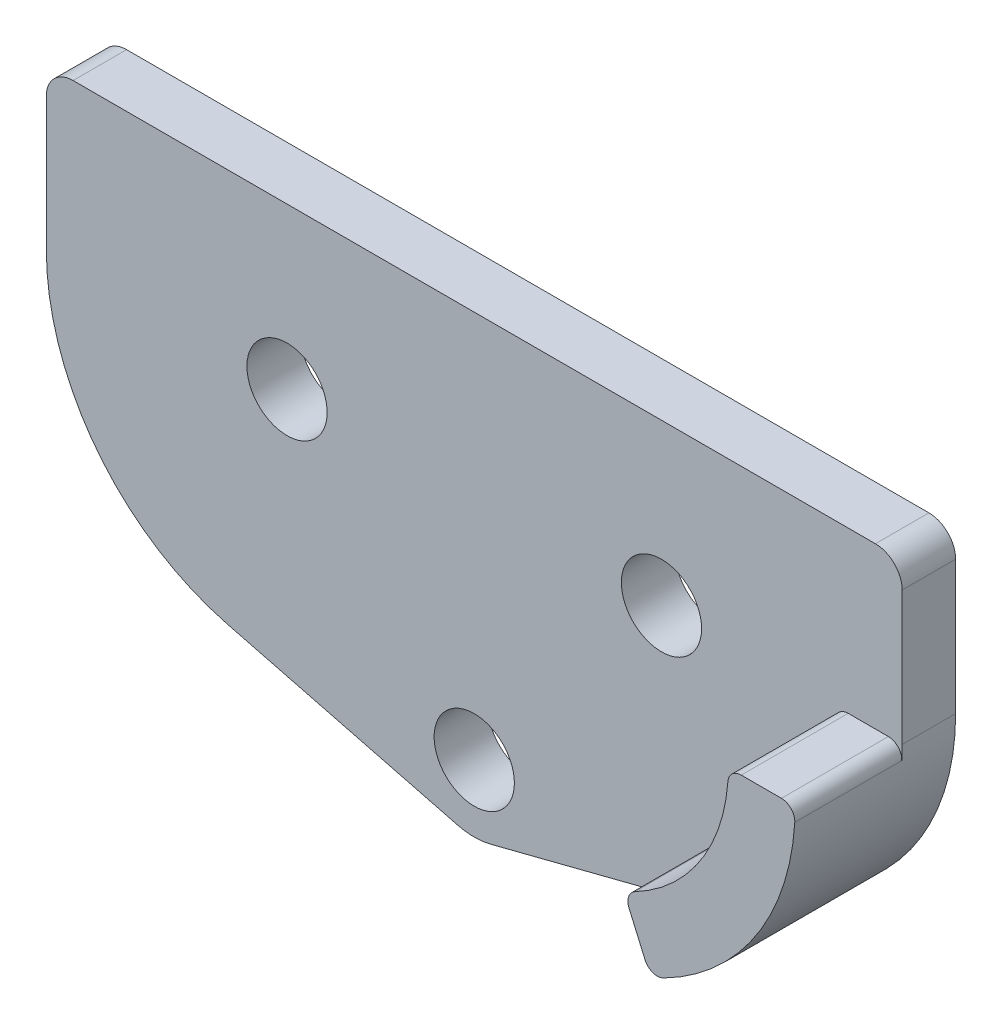
SolidWorks part; units mm, degrees
ref_plane "前视基准面" through (0, 0, 0) normal (0, 0, 1) x (1, 0, 0)
ref_plane "上视基准面" through (0, 0, 0) normal (0, 1, 0) x (1, 0, 0)
ref_plane "右视基准面" through (0, 0, 0) normal (1, 0, 0) x (0, 0, -1)
sketch "草图2" plane through (0, 0, 0) normal (0, 0, 1) x (1, 0, 0)
  line L0 (0, 6.5192) -> (0, -8.5) construction
  line L1 (0, 0) -> (7, 0) construction
  line L2 (0, -6) -> (7, -6) construction
  line L3 (7, 6) -> (-7, 6)
  line L4 (16, 0) -> (16, 6)
  line L5 (16, 6) -> (7, 6)
  line L6 (9.2305, -8.7192) -> (0.6196, -10.922)
  line L7 (0, -8.5) -> (0, -16) construction
  line L8 (-9.2305, -8.7192) -> (-0.6196, -10.922)
  line L9 (-16, 0) -> (-16, 6)
  line L10 (-16, 6) -> (-7, 6)
  circle A0 centre (7, 0) radius 6 construction
  circle A1 centre (0, -8.5) radius 1.5
  circle A2 centre (7, 0) radius 1.5
  circle A5 centre (0, -8.5) radius 2.5 construction
  arc A6 (9.2305, -8.7192) -> (16, 0) centre (7, 0) ccw
  arc A7 (0.6196, -10.922) -> (-0.6196, -10.922) centre (0, -8.5) cw
  circle A8 centre (-7, 0) radius 1.5
  arc A9 (-9.2305, -8.7192) -> (-16, 0) centre (-7, 0) cw
  point P25 (0, 6)
  dimension "D2" = 12
  dimension "D3" = 3
  dimension "D5" = 3
  dimension "D6" = 9
  dimension "D7" = 5
  dimension "D1" = 7
  dimension "D4" = 2.5
extrude "凸台-拉伸1" add sketch "草图2" along normal blind 2
sketch "草图3" plane through (0, 0, 2) normal (0, 0, 1) x (1, 0, 0)
  line L3 (13.5, 0) -> (16, 0)
  line L4 (7, 0) -> (10.5919, -8.2522) construction
  line L5 (9.5942, -5.9599) -> (10.5919, -8.2522)
  arc A0 (9.5942, -5.9599) -> (13.5, 0) centre (7, 0) ccw
  arc A2 (10.5919, -8.2522) -> (16, 0) centre (7, 0) ccw
  dimension "D1" = 13
  dimension "D2" = 9
extrude "凸台-拉伸2" add sketch "草图3" along normal blind 4
fillet "圆角1" radius 1 2 edges at (-16, 6, 1) (16, 6, 1)
fillet "圆角4" radius 0.5 4 edges at (9.5942, -5.9599, 4) (10.5919, -8.2522, 4) (16, 0, 4) (13.5, 0, 4)
